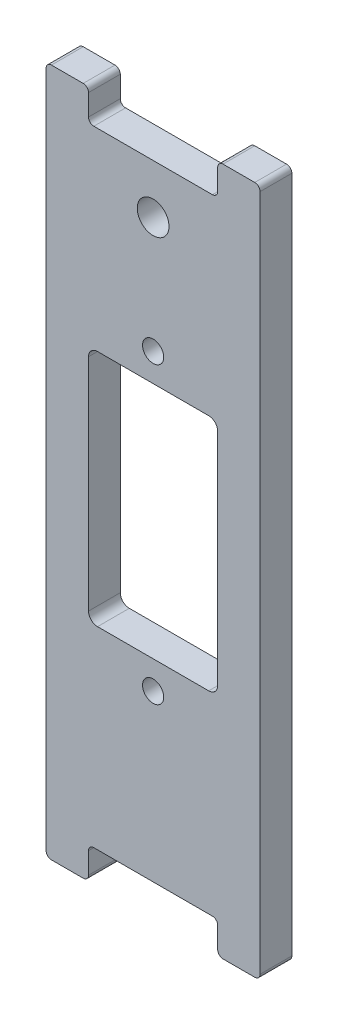
SolidWorks part; units mm, degrees
ref_plane "Front Plane" through (0, 0, 0) normal (0, 0, 1) x (1, 0, 0)
ref_plane "Top Plane" through (0, 0, 0) normal (0, 1, 0) x (1, 0, 0)
ref_plane "Right Plane" through (0, 0, 0) normal (1, 0, 0) x (0, 0, -1)
sketch "Sketch1" plane through (0, 0, 0) normal (0, 0, 1) x (1, 0, 0)
  line L0 (-10.1, 0) -> (0, 0) construction
  line L1 (5.6, -29.5) -> (-5.6, -29.5)
  line L2 (10.1, -22.5) -> (10.1, 22.5)
  line L3 (5.6, 29.5) -> (-5.6, 29.5)
  line L4 (-10.1, -22.5) -> (-10.1, 22.5)
  line L5 (10.1, -22.5) -> (-10.1, 22.5) construction
  line L6 (10.1, 22.5) -> (-10.1, -22.5) construction
  line L7 (5.25, -11.25) -> (-5.25, -11.25)
  line L8 (6.1, -10.4) -> (6.1, 10.4)
  line L9 (5.25, 11.25) -> (-5.25, 11.25)
  line L10 (-6.1, -10.4) -> (-6.1, 10.4)
  line L11 (6.1, -11.25) -> (-6.1, 11.25) construction
  line L12 (6.1, 11.25) -> (-6.1, -11.25) construction
  line L13 (0, 0) -> (0, 13.9) construction
  line L15 (-10.1, 22.5) -> (-10.1, 32)
  line L16 (-9.6, 32.5) -> (-6.6, 32.5)
  line L17 (-6.1, 30) -> (-6.1, 32)
  line L18 (9.6, 32.5) -> (6.6, 32.5)
  line L19 (6.1, 30) -> (6.1, 32)
  line L21 (10.1, 22.5) -> (10.1, 32)
  line L23 (6.1, -30) -> (6.1, -32)
  line L24 (9.6, -32.5) -> (6.6, -32.5)
  line L25 (10.1, -22.5) -> (10.1, -32)
  line L26 (-9.6, -32.5) -> (-6.6, -32.5)
  line L27 (-6.1, -30) -> (-6.1, -32)
  line L29 (-10.1, -22.5) -> (-10.1, -32)
  circle A0 centre (0, 13.9) radius 1
  circle A2 centre (0, -13.9) radius 1
  arc A3 (-9.6, -32.5) -> (-10.1, -32) centre (-9.6, -32) cw
  arc A4 (-6.6, -32.5) -> (-6.1, -32) centre (-6.6, -32) ccw
  arc A5 (-6.1, -30) -> (-5.6, -29.5) centre (-5.6, -30) cw
  arc A6 (5.6, -29.5) -> (6.1, -30) centre (5.6, -30) cw
  arc A7 (6.1, -32) -> (6.6, -32.5) centre (6.6, -32) ccw
  arc A8 (9.6, -32.5) -> (10.1, -32) centre (9.6, -32) ccw
  arc A9 (10.1, 32) -> (9.6, 32.5) centre (9.6, 32) ccw
  arc A10 (6.6, 32.5) -> (6.1, 32) centre (6.6, 32) ccw
  arc A11 (6.1, 30) -> (5.6, 29.5) centre (5.6, 30) cw
  arc A12 (-5.6, 29.5) -> (-6.1, 30) centre (-5.6, 30) cw
  arc A13 (-6.6, 32.5) -> (-6.1, 32) centre (-6.6, 32) cw
  arc A14 (-10.1, 32) -> (-9.6, 32.5) centre (-9.6, 32) cw
  arc A15 (5.25, -11.25) -> (6.1, -10.4) centre (5.25, -10.4) ccw
  arc A16 (-5.25, -11.25) -> (-6.1, -10.4) centre (-5.25, -10.4) cw
  arc A17 (-5.25, 11.25) -> (-6.1, 10.4) centre (-5.25, 10.4) ccw
  arc A18 (6.1, 10.4) -> (5.25, 11.25) centre (5.25, 10.4) ccw
  circle A19 centre (0, -5.15) radius 1.5 construction
  circle A21 centre (0, 24.85) radius 1.5
  point P0 (0, 0)
  point P6 (0, 0)
  point P31 (-10.1, -32.5)
  point P34 (-6.1, -32.5)
  point P37 (-6.1, -29.5)
  point P40 (6.1, -29.5)
  point P43 (6.1, -32.5)
  point P46 (10.1, -32.5)
  point P49 (10.1, 32.5)
  point P52 (6.1, 32.5)
  point P55 (6.1, 29.5)
  point P58 (-6.1, 29.5)
  point P61 (-6.1, 32.5)
  point P64 (-10.1, 32.5)
  dimension "D5" = 2
  dimension "D6" = 27.8
  dimension "D8" = 0.5
  dimension "D10" = 0.85
  dimension "D11" = 3
  dimension "D13" = 3
  dimension "D1" = 45
  dimension "D2" = 20.2
  dimension "D3" = 22.5
  dimension "D4" = 12.2
  dimension "D7" = 3
  dimension "D9" = 65
  dimension "D12" = 16.4
  dimension "D14" = 30
extrude "Boss-Extrude1" add sketch "Sketch1" along normal blind 3
